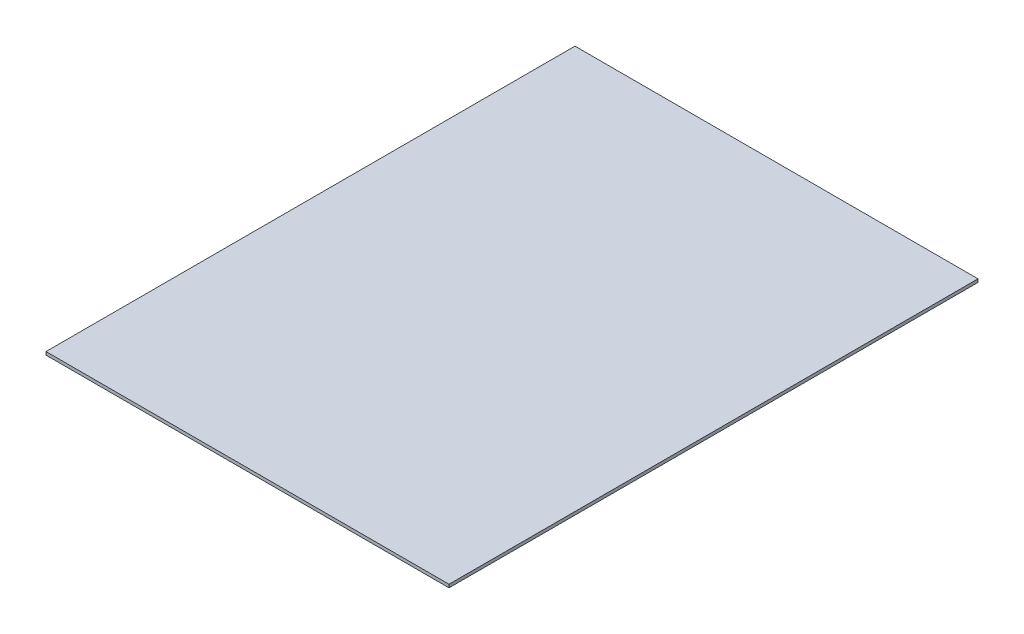
SolidWorks part; units mm, degrees
material "Acrylic (Medium-high impact)"
ref_plane "Front Plane" through (0, 0, 0) normal (0, 0, 1) x (1, 0, 0)
ref_plane "Top Plane" through (0, 0, 0) normal (0, 1, 0) x (1, 0, 0)
ref_plane "Right Plane" through (0, 0, 0) normal (1, 0, 0) x (0, 0, -1)
sketch "Sketch1" plane through (0, 0, 0) normal (0, 1, 0) x (1, 0, 0)
  line L1 (-203.2, -266.7) -> (203.2, -266.7)
  line L2 (-203.2, -266.7) -> (-203.2, 266.7)
  line L3 (-203.2, 266.7) -> (203.2, 266.7)
  line L4 (203.2, -266.7) -> (203.2, 266.7)
  line L5 (-203.2, -266.7) -> (203.2, 266.7) construction
  line L6 (-203.2, 266.7) -> (203.2, -266.7) construction
  point P0 (0, 0)
  dimension "D1" = 533.4
  dimension "D2" = 406.4
extrude "Boss-Extrude1" add sketch "Sketch1" along normal blind 3.175
